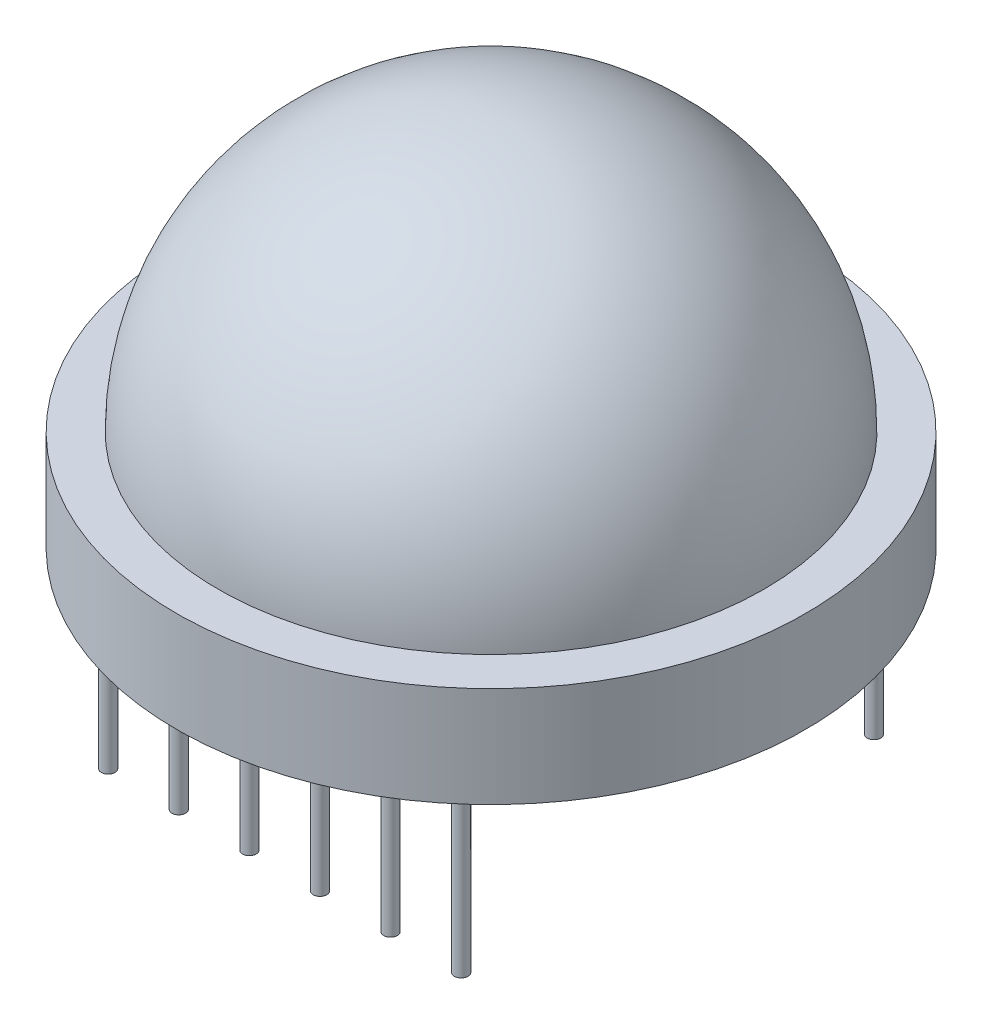
SolidWorks part; units mm, degrees
ref_plane "Front Plane" through (0, 0, 0) normal (0, 0, 1) x (1, 0, 0)
ref_plane "Top Plane" through (0, 0, 0) normal (0, 1, 0) x (1, 0, 0)
ref_plane "Right Plane" through (0, 0, 0) normal (1, 0, 0) x (0, 0, -1)
sketch "Sketch1" plane through (0, 0, 0) normal (0, 0, 1) x (1, 0, 0)
  line L0 (0, 10.055) -> (0, 0)
  line L1 (0, 0) -> (0, -3.7)
  line L2 (0, -3.7) -> (-11.595, -3.7)
  line L3 (-11.595, -3.7) -> (-11.595, 0)
  line L4 (-11.595, 0) -> (-10.055, 0)
  line L5 (0, -3.7) -> (11.595, -3.7) construction
  line L6 (-10.055, 0) -> (10.055, 0) construction
  arc A0 (-10.055, 0) -> (0, 10.055) centre (0, 0) cw
  point P6 (0, 0)
  dimension "D1" = 23.19
  dimension "D2" = 20.11
  dimension "D3" = 3.7
  dimension "D4" = 13.755
revolve "Revolve1" add sketch "Sketch1" angle 360 about L0
sketch "Sketch2" plane through (0, -3.7, 0) normal (0, -1, 0) x (1, 0, 0)
  line L0 (-6.505, 7.855) -> (-6.505, -7.855) construction
  line L1 (-6.755, 7.605) -> (6.755, 7.605) construction
  line L2 (0, 7.605) -> (0, -7.605) construction
  line L3 (-6.505, -7.605) -> (6.505, -7.605) construction
  circle A0 centre (-6.505, 7.605) radius 0.25
  circle A1 centre (-3.903, 7.605) radius 0.25
  circle A2 centre (-1.301, 7.605) radius 0.25
  circle A3 centre (1.301, 7.605) radius 0.25
  circle A4 centre (3.903, 7.605) radius 0.25
  circle A5 centre (6.505, 7.605) radius 0.25
  circle A6 centre (-3.903, -7.605) radius 0.25
  circle A7 centre (-1.301, -7.605) radius 0.25
  circle A8 centre (1.301, -7.605) radius 0.25
  circle A9 centre (3.903, -7.605) radius 0.25
  circle A10 centre (6.505, -7.605) radius 0.25
  circle A11 centre (-6.505, -7.605) radius 0.25
  point P30 (0, 0)
  dimension "D5" = 0.5
  dimension "D3" = 15.71
  dimension "D4" = 13.51
  dimension "D1" = 6
  dimension "D2" = 2
extrude "Boss-Extrude1" add sketch "Sketch2" along normal blind 6.5
